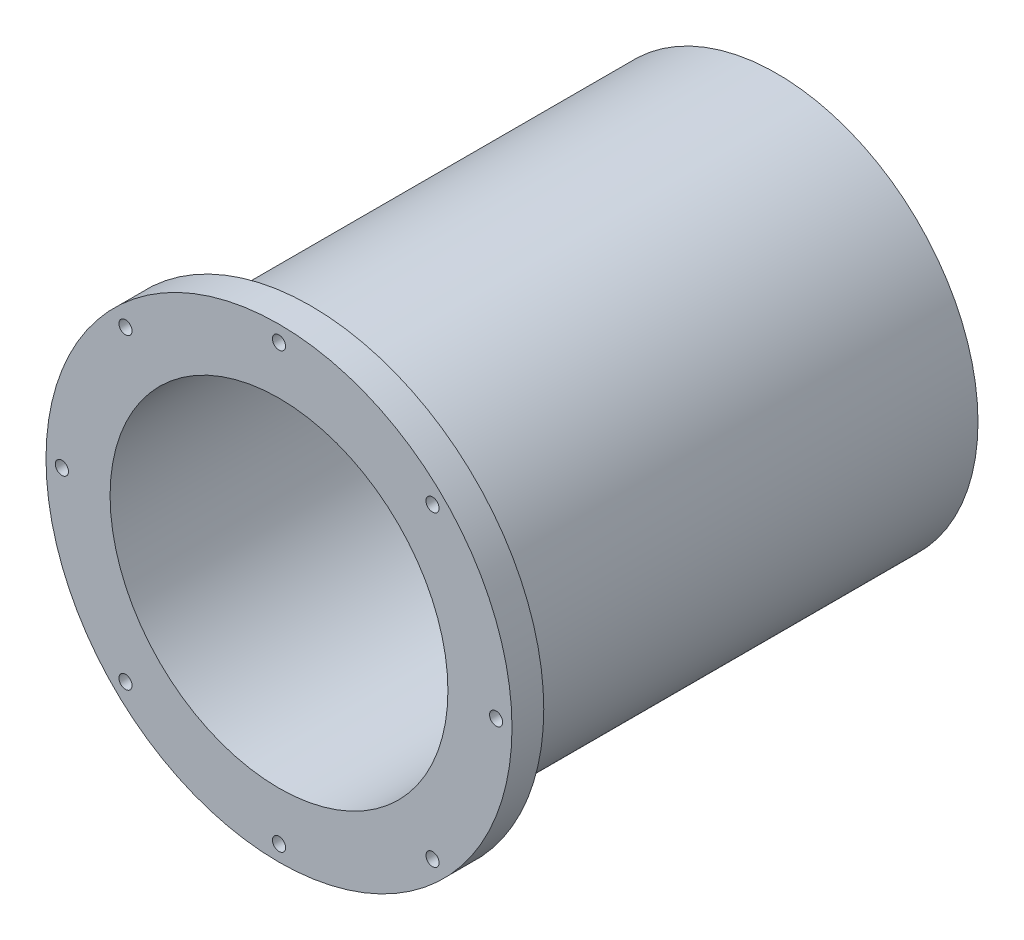
SolidWorks part; units mm, degrees
ref_plane "Ön Düzlem" through (0, 0, 0) normal (0, 0, 1) x (1, 0, 0)
ref_plane "Üst Düzlem" through (0, 0, 0) normal (0, 1, 0) x (1, 0, 0)
ref_plane "Sağ Düzlem" through (0, 0, 0) normal (1, 0, 0) x (0, 0, -1)
sketch "Çizim1" plane through (0, 0, 0) normal (0, 0, 1) x (1, 0, 0)
  circle A0 centre (0, 0) radius 55
  dimension "D1" = 110
extrude "Yükseklik-Ekstrüzyon1" add sketch "Çizim1" along normal mid plane 22
sketch "Çizim2" plane through (0, 0, -11) normal (0, 0, -1) x (-1, 0, 0)
  circle A0 centre (0, 0) radius 47.5
  dimension "D1" = 95
extrude "Kes-Ekstrüzyon1" cut sketch "Çizim2" against normal blind 14.5 flip side to cut
sketch "Çizim3" plane through (0, 0, 3.5) normal (0, 0, -1) x (-1, 0, 0)
  circle A0 centre (0, 0) radius 51.25 construction
  circle A1 centre (0, 51.25) radius 1.55
  dimension "D1" = 102.5
  dimension "D2" = 3.1
extrude "Kes-Ekstrüzyon2" cut sketch "Çizim3" against normal through all
pattern_circular "Dairesel Kaplama1" count 8 over 360 about axis through (0, 0, 0) along (0, 0, 1) of "Kes-Ekstrüzyon2"
sketch "Çizim4" plane through (0, 0, 11) normal (0, 0, 1) x (1, 0, 0)
  circle A0 centre (0, 0) radius 39.875
  dimension "D1" = 79.75
extrude "Kes-Ekstrüzyon3" cut sketch "Çizim4" against normal through all
sketch "Çizim5" plane through (0, 0, -11) normal (0, 0, -1) x (-1, 0, 0)
  circle A0 centre (0, 0) radius 39.875 construction
  circle A1 centre (0, 0) radius 47.5
  circle A2 centre (0, 0) radius 47.5
  circle A3 centre (0, 0) radius 39.875
  dimension "D1" = 0
extrude "Yükseklik-Ekstrüzyon2" add sketch "Çizim5" along normal blind 95.5
